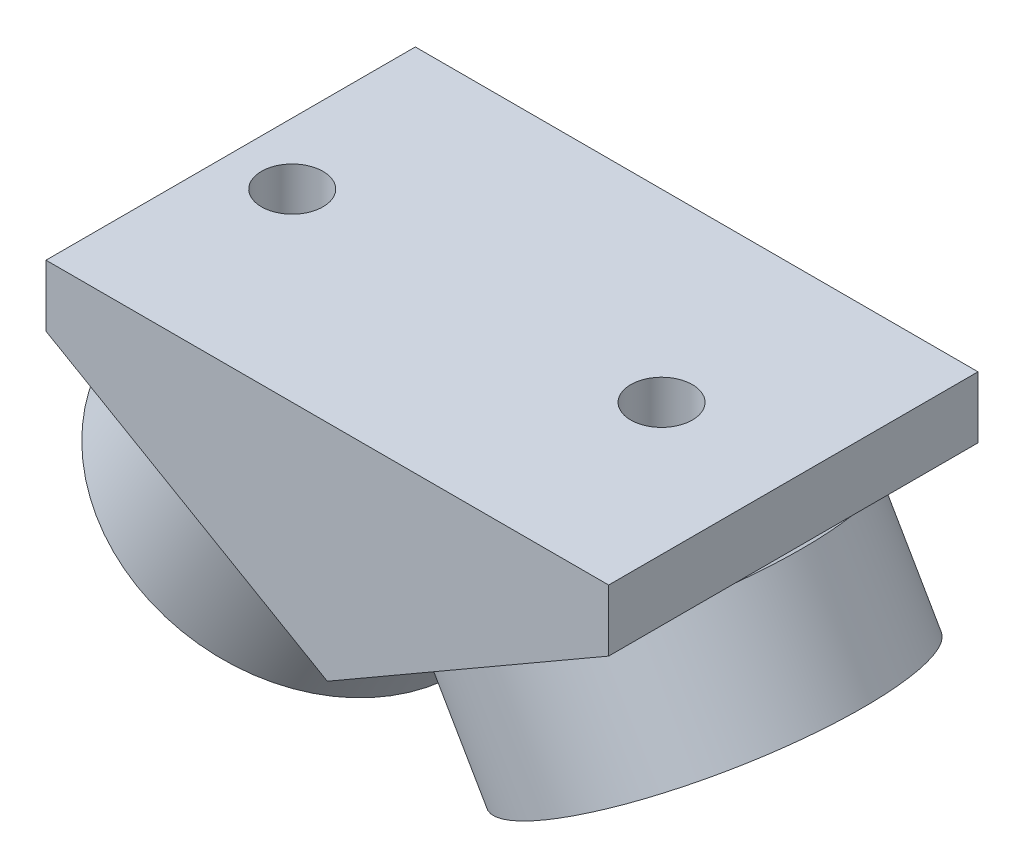
SolidWorks part; units mm, degrees
ref_plane "Front Plane" through (0, 0, 0) normal (0, 0, 1) x (1, 0, 0)
ref_plane "Top Plane" through (0, 0, 0) normal (0, 1, 0) x (1, 0, 0)
ref_plane "Right Plane" through (0, 0, 0) normal (1, 0, 0) x (0, 0, -1)
sketch "Sketch1" plane through (0, 0, 0) normal (0, 0, 1) x (1, 0, 0)
  line L3 (-29.0219, 16.7558) -> (-29.0219, 23.1058)
  line L4 (-29.0219, 23.1058) -> (29.0219, 23.1058)
  line L5 (29.0219, 23.1058) -> (29.0219, 16.7558)
  line L7 (-29.0219, 16.7558) -> (0, 0)
  line L8 (0, 0) -> (29.0219, 16.7558)
  dimension "D1" = 120
  dimension "D2" = 6.35
extrude "Boss-Extrude1" add sketch "Sketch1" along normal blind 38.1
sketch "Sketch4" plane through (0, 0, 0) normal (-0.5, -0.866, 0) x (0.866, -0.5, 0)
  line L0 (-33.5116, 38.1) -> (0, 0) construction
  line L1 (0, 38.1) -> (-33.5116, 0) construction
  circle A0 centre (-16.7558, 19.05) radius 13.97
  circle A1 centre (-16.7558, 19.05) radius 17.78
  point P9 (-16.7558, 19.05)
  dimension "D1" = 27.94
  dimension "D2" = 35.56
extrude "Boss-Extrude3" add sketch "Sketch4" along normal blind 12.7
ref_plane "Plane2" through (0, 0, 0) normal (-1, 0, 0) x (0, 0, 1)
mirror "Mirror2" about plane through (0, 0, 0) normal (-1, 0, 0) of "Boss-Extrude3"
sketch "Sketch5" plane through (0, 23.1058, 0) normal (0, 1, 0) x (1, 0, 0)
  line L1 (-29.0219, -24.9974) -> (-29.0219, -13.1026) construction
  line L2 (29.0219, 0) -> (-29.0219, 0) construction
  circle A0 centre (-22.6719, -19.05) radius 3.175
  circle A1 centre (15.4281, -19.05) radius 3.175
  dimension "D2" = 6.35
  dimension "D3" = 6.35
  dimension "D1" = 38.1
  dimension "D4" = 19.05
extrude "Cut-Extrude2" cut sketch "Sketch5" against normal blind 12.7
ref_plane "Plane1" through (0, 0, 0) normal (-1, 0, 0) x (0, 0, 1)
